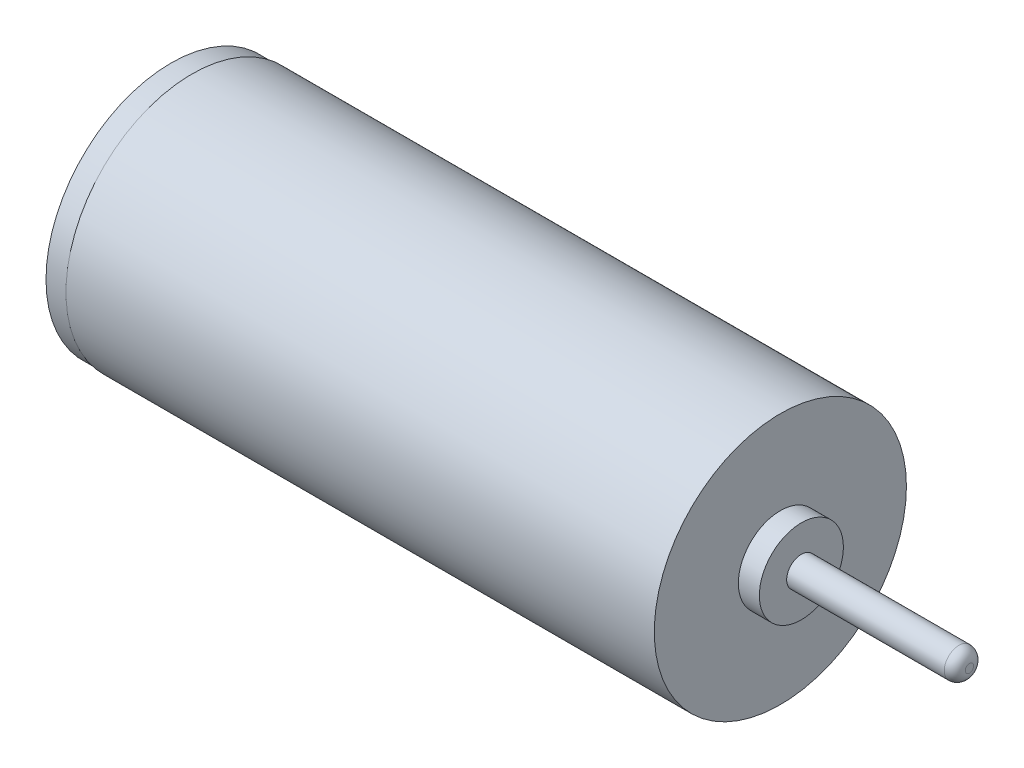
SolidWorks part; units mm, degrees
ref_plane "Front Plane" through (0, 0, 0) normal (0, 0, 1) x (1, 0, 0)
ref_plane "Top Plane" through (0, 0, 0) normal (0, 1, 0) x (1, 0, 0)
ref_plane "Right Plane" through (0, 0, 0) normal (1, 0, 0) x (0, 0, -1)
sketch "Sketch1" plane through (0, 0, 0) normal (1, 0, 0) x (0, 0, -1)
  circle A1 centre (0, 0) radius 3
  dimension "D1" = 6
extrude "Boss-Extrude1" add sketch "Sketch1" against normal blind 14
sketch "Sketch2" plane through (0, 0, 0) normal (1, 0, 0) x (0, 0, -1)
  circle A0 centre (0, 0) radius 1
  dimension "D1" = 2
extrude "Boss-Extrude2" add sketch "Sketch2" along normal blind 0.5
sketch "Sketch3" plane through (0.5, 0, 0) normal (1, 0, 0) x (0, 0, -1)
  circle A0 centre (0, 0) radius 0.35
  dimension "D1" = 0.7
extrude "Boss-Extrude3" add sketch "Sketch3" along normal blind 4
fillet "Fillet1" radius 0.25 1 edges at (4.5, 0, -0.35)
sketch "Sketch7" plane through (-14, 0, 0) normal (-1, 0, 0) x (0, 0, 1)
  circle A0 centre (0, 0) radius 2.975
  dimension "D1" = 5.95
extrude "Boss-Extrude6" add sketch "Sketch7" along normal blind 0.5
sketch "Sketch8" plane through (-14.5, 0, 0) normal (-1, 0, 0) x (0, 0, 1)
  circle A0 centre (0, 0) radius 1
  dimension "D1" = 2
extrude "Boss-Extrude7" add sketch "Sketch8" along normal blind 1
